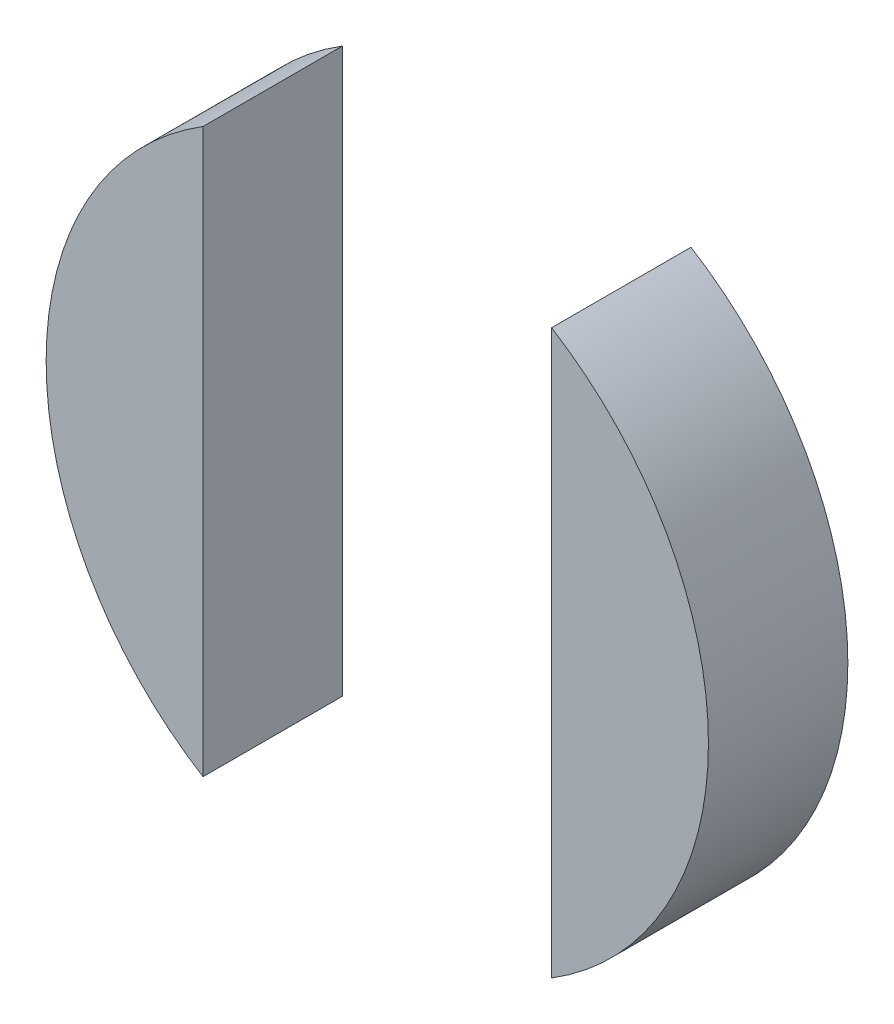
SolidWorks part; units mm, degrees
ref_plane "Front Plane" through (0, 0, 0) normal (0, 0, 1) x (1, 0, 0)
ref_plane "Top Plane" through (0, 0, 0) normal (0, 1, 0) x (1, 0, 0)
ref_plane "Right Plane" through (0, 0, 0) normal (1, 0, 0) x (0, 0, -1)
sketch "Sketch1" plane through (0, 0, 0) normal (0, 0, 1) x (1, 0, 0)
  line L0 (-5, 8.0777) -> (-5, -8.0777)
  line L1 (5, 8.0777) -> (5, -8.0777)
  circle A0 centre (0, 0) radius 9.5 construction
  arc A2 (-5, 8.0777) -> (-5, -8.0777) centre (0, 0) ccw
  arc A3 (5, 8.0777) -> (5, -8.0777) centre (0, 0) cw
  dimension "D1" = 19
  dimension "D3" = 5
  dimension "D4" = 5
extrude "Boss-Extrude1" add sketch "Sketch1" along normal blind 4
